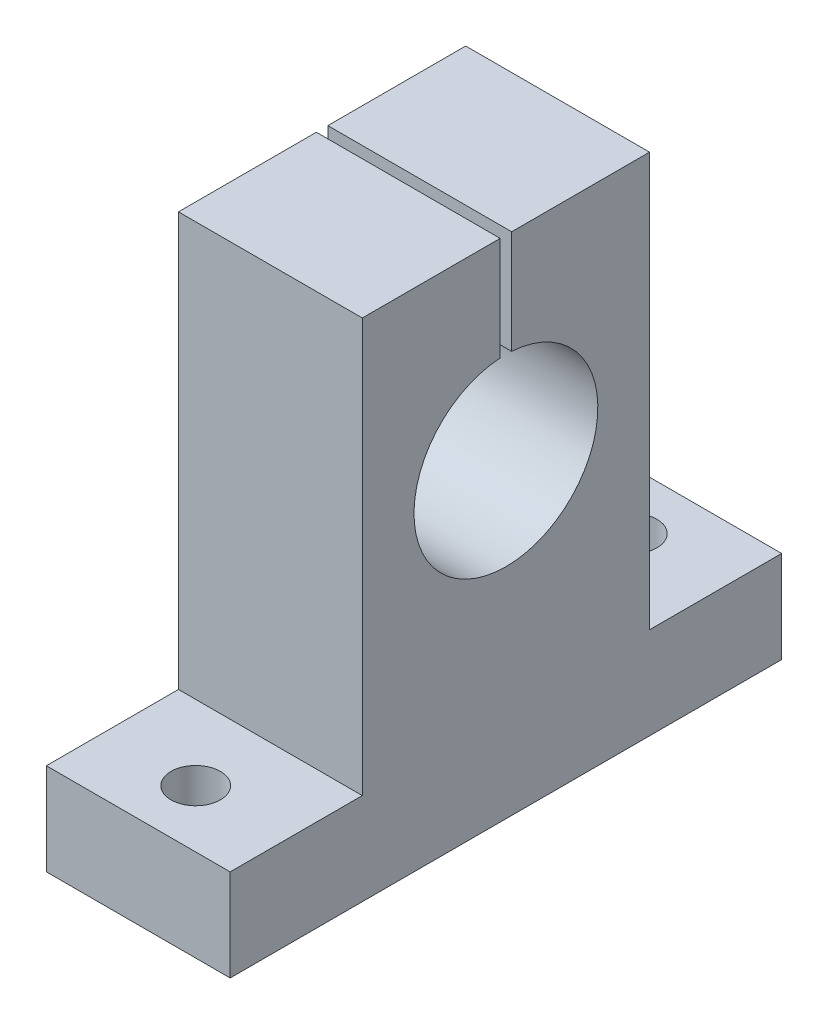
SolidWorks part; units mm, degrees
ref_plane "Front Plane" through (0, 0, 0) normal (0, 0, 1) x (1, 0, 0)
ref_plane "Top Plane" through (0, 0, 0) normal (0, 1, 0) x (1, 0, 0)
ref_plane "Right Plane" through (0, 0, 0) normal (1, 0, 0) x (0, 0, -1)
sketch "Sketch1" plane through (0, 0, 0) normal (1, 0, 0) x (0, 0, -1)
  line L0 (0, 40.701) -> (0, -61.3006) construction
  line L1 (12.5, 8) -> (24, 8)
  line L2 (-24, 0) -> (24, 0)
  line L3 (-24, 0) -> (-24, 8)
  line L4 (-24, 8) -> (-12.5, 8)
  line L5 (24, 0) -> (24, 8)
  line L7 (-12.5, 8) -> (-12.5, 44)
  line L8 (-12.5, 44) -> (-0.5, 44)
  line L9 (12.5, 8) -> (12.5, 44)
  line L10 (0.5, 44) -> (12.5, 44)
  line L12 (-0.5, 44) -> (-0.5, 34.9844)
  line L14 (0.5, 44) -> (0.5, 34.9844)
  arc A0 (-0.5, 34.9844) -> (0.5, 34.9844) centre (0, 27) ccw
  dimension "D4" = 16
  dimension "D1" = 48
  dimension "D2" = 8
  dimension "D3" = 44
  dimension "D5" = 27
  dimension "D6" = 25
  dimension "D7" = 1
extrude "Boss-Extrude1" add sketch "Sketch1" along normal blind 16
sketch "Sketch2" plane through (0, 8, 0) normal (0, 1, 0) x (1, 0, 0)
  line L2 (16, -24) -> (0, -24) construction
  line L3 (0, -12.5) -> (0, -24) construction
  point P3 (8, -19)
  dimension "D3" = 5
  dimension "D4" = 8
sketch "Sketch7" plane through (0, 8, 0) normal (0, 1, 0) x (1, 0, 0)
  line L0 (16, 24) -> (0, 24) construction
  point P0 (8, 19)
  dimension "D1" = 5
hole_wizard "M4 Clearance Hole2" positions "Sketch8" profile "Sketch9" hole size "M4" standard "IS" end condition through all
sketch "Sketch8" plane through (0, 8, 0) normal (0, 1, 0) x (1, 0, 0)
  point P0 (8, 19)
  point P5 (8, -19)
sketch "Sketch9" plane through (8, 8, -19) normal (1, 0, 0) x (0, 0, 1)
  line L0 (0, 0) -> (0, 8)
  line L1 (0, 8) -> (2.15, 8)
  line L2 (2.15, 8) -> (2.15, 0)
  line L5 (2.15, 0) -> (0, 0)
  line L11 (0, -6.35) -> (0, 107.95) construction
  dimension "Thru Hole Dia." = 4.3
  dimension "Thru Hole Depth" = 8
